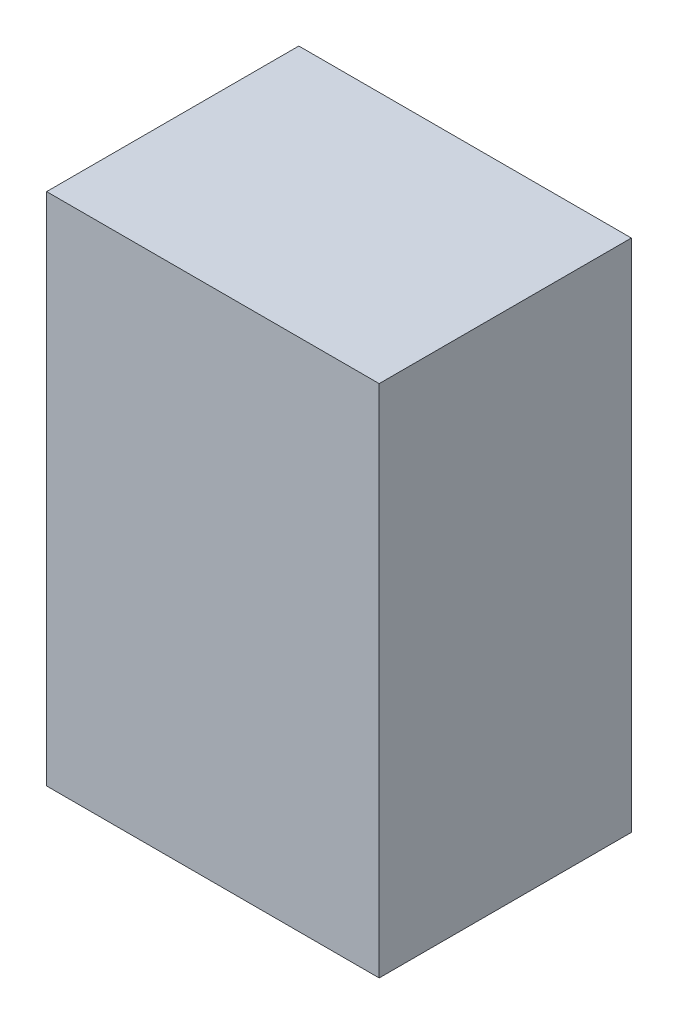
SolidWorks part; units mm, degrees
ref_plane "Front Plane" through (0, 0, 0) normal (0, 0, 1) x (1, 0, 0)
ref_plane "Top Plane" through (0, 0, 0) normal (0, 1, 0) x (1, 0, 0)
ref_plane "Right Plane" through (0, 0, 0) normal (1, 0, 0) x (0, 0, -1)
sketch "Sketch1" plane through (0, 0, 0) normal (0, 0, 1) x (1, 0, 0)
  line L1 (121.92, -188.722) -> (-121.92, -188.722)
  line L2 (121.92, -188.722) -> (121.92, 188.722)
  line L3 (121.92, 188.722) -> (-121.92, 188.722)
  line L4 (-121.92, -188.722) -> (-121.92, 188.722)
  line L5 (121.92, -188.722) -> (-121.92, 188.722) construction
  line L6 (121.92, 188.722) -> (-121.92, -188.722) construction
  point P0 (0, 0)
  dimension "D1" = 243.84
  dimension "D2" = 377.444
extrude "Boss-Extrude1" add sketch "Sketch1" along normal blind 184.912
